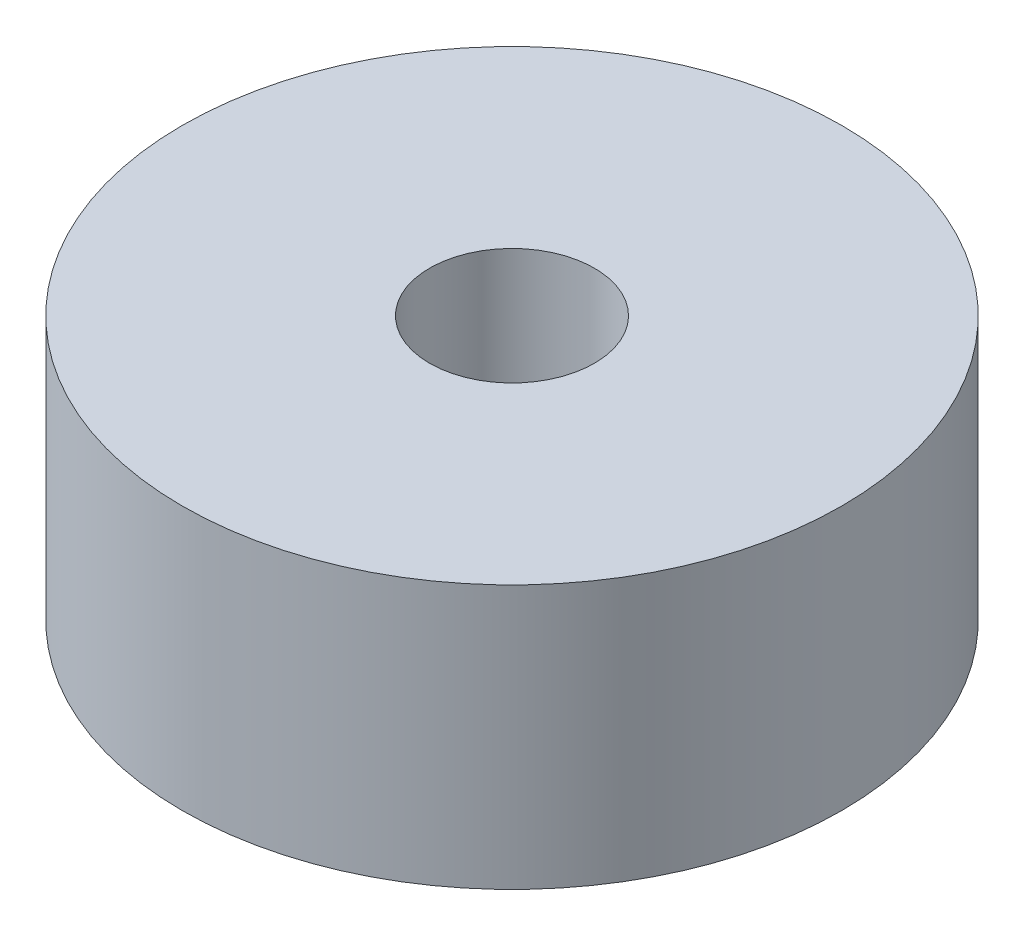
SolidWorks part; units mm, degrees
material "1060-H12 棒材(SS)"
ref_plane "前视基准面" through (0, 0, 0) normal (0, 0, 1) x (1, 0, 0)
ref_plane "上视基准面" through (0, 0, 0) normal (0, 1, 0) x (1, 0, 0)
ref_plane "右视基准面" through (0, 0, 0) normal (1, 0, 0) x (0, 0, -1)
sketch "草图1" plane through (0, 0, 0) normal (0, 1, 0) x (1, 0, 0)
  circle A0 centre (0, 0) radius 10
  dimension "D1" = 20
extrude "凸台-拉伸1" add sketch "草图1" along normal blind 8
sketch "草图2" plane through (0, 8, 0) normal (0, 1, 0) x (1, 0, 0)
  circle A0 centre (0, 0) radius 2.5
  dimension "D1" = 5
extrude "切除-拉伸1" cut sketch "草图2" against normal blind 8
